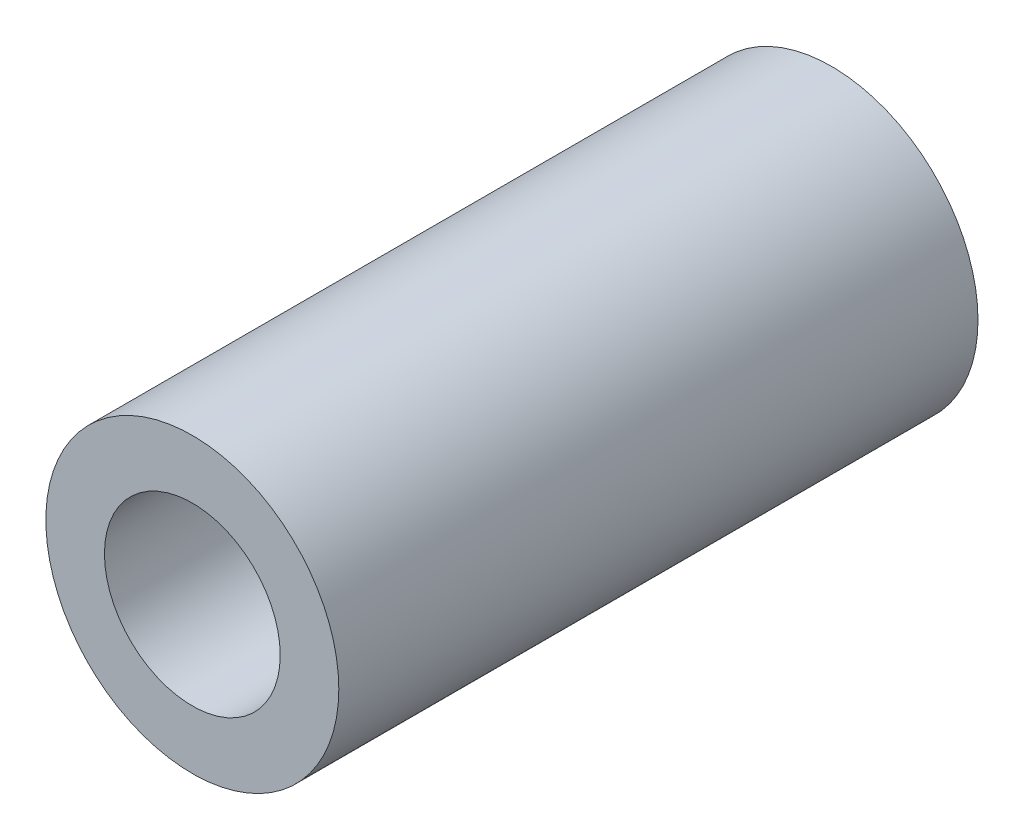
SolidWorks part; units mm, degrees
material "6061 合金"
ref_plane "前视基准面" through (0, 0, 0) normal (0, 0, 1) x (1, 0, 0)
ref_plane "上视基准面" through (0, 0, 0) normal (0, 1, 0) x (1, 0, 0)
ref_plane "右视基准面" through (0, 0, 0) normal (1, 0, 0) x (0, 0, -1)
sketch "草图1" plane through (0, 0, 0) normal (0, 0, 1) x (1, 0, 0)
  circle A1 centre (0, 0) radius 2.75
  dimension "D1" = 5.5
extrude "凸台-拉伸1" add sketch "草图1" along normal blind 12
hole_wizard "M4 螺纹孔1" positions "草图2" profile "草图3" tap size "M4" standard "GB" end condition through all
sketch "草图2" plane through (0, 0, 12) normal (0, 0, 1) x (1, 0, 0)
  point P0 (0, 0)
sketch "草图3" plane through (0, 0, 12) normal (1, 0, 0) x (0, -1, 0)
  line L0 (0, 0) -> (0, 12)
  line L1 (0, 12) -> (1.65, 12)
  line L2 (1.65, 12) -> (1.65, 0)
  line L5 (1.65, 0) -> (0, 0)
  line L11 (0, -6.35) -> (0, 107.95) construction
  dimension "通孔螺纹孔钻头直径" = 3.3
  dimension "通孔螺纹孔钻头深度" = 12
cosmetic thread "孔螺蚊线1"
